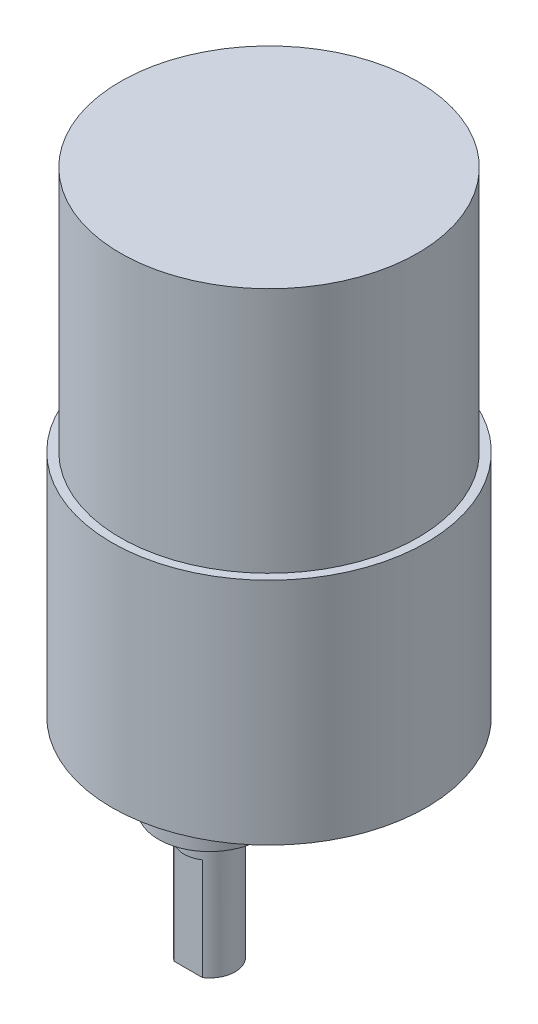
SolidWorks part; units mm, degrees
ref_plane "Ebene vorne" through (0, 0, 0) normal (0, 0, 1) x (1, 0, 0)
ref_plane "Ebene oben" through (0, 0, 0) normal (0, 1, 0) x (1, 0, 0)
ref_plane "Ebene rechts" through (0, 0, 0) normal (1, 0, 0) x (0, 0, -1)
sketch "Skizze1" plane through (0, 0, 0) normal (0, 1, 0) x (1, 0, 0)
  circle A0 centre (0, 0) radius 18.5
  dimension "D1" = 37
extrude "Aufsatz-Linear austragen1" add sketch "Skizze1" along normal blind 27
sketch "Skizze2" plane through (0, 27, 0) normal (0, 1, 0) x (1, 0, 0)
  circle A0 centre (0, 0) radius 17.5
  dimension "D1" = 35
extrude "Aufsatz-Linear austragen2" add sketch "Skizze2" along normal blind 29
sketch "Skizze3" plane through (0, 0, 0) normal (0, -1, 0) x (1, 0, 0)
  line L0 (0, 0) -> (50000, 0) construction
  line L1 (0, 0) -> (0, 50000) construction
  line L2 (7.75, -13.4234) -> (-7.75, 13.4234) construction
  line L3 (-7.75, -13.4234) -> (7.75, 13.4234) construction
  circle A0 centre (0, 0) radius 15.5 construction
  circle A1 centre (-15.5, 0) radius 1.5
  circle A2 centre (15.5, 0) radius 1.5
  circle A3 centre (7.75, 13.4234) radius 1.5
  circle A4 centre (-7.75, 13.4234) radius 1.5
  circle A5 centre (-7.75, -13.4234) radius 1.5
  circle A6 centre (7.75, -13.4234) radius 1.5
  point P14 (0, 0)
  point P17 (0, 0)
  point P21 (-18.9197, 0)
  dimension "D1" = 31
  dimension "D2" = 3
  dimension "D3" = 30
  dimension "D4" = 30
extrude "Schnitt-Linear austragen1" cut sketch "Skizze3" against normal blind 10
sketch "Skizze4" plane through (0, 0, 0) normal (0, -1, 0) x (1, 0, 0)
  line L0 (0, 0) -> (0, 18.5) construction
  circle A0 centre (0, 0) radius 18.5 construction
  circle A1 centre (0, 7) radius 6
  dimension "D1" = 12
  dimension "D2" = 7
extrude "Aufsatz-Linear austragen3" add sketch "Skizze4" along normal blind 6
sketch "Skizze5" plane through (0, -6, 0) normal (0, -1, 0) x (1, 0, 0)
  circle A0 centre (0, 7) radius 3
  dimension "D1" = 6
extrude "Aufsatz-Linear austragen4" add sketch "Skizze5" along normal blind 15
sketch "Skizze6" plane through (0, -21, 0) normal (0, -1, 0) x (1, 0, 0)
  line L0 (0, 7) -> (0, 10) construction
  line L1 (-3, 10.5) -> (3, 10.5)
  line L2 (-3, 10.5) -> (-3, 9.5)
  line L3 (-3, 9.5) -> (3, 9.5)
  line L4 (3, 10.5) -> (3, 9.5)
  line L5 (-3, 10.5) -> (3, 9.5) construction
  line L6 (-3, 9.5) -> (3, 10.5) construction
  circle A3 centre (0, 7) radius 3 construction
  circle A4 centre (0, 7) radius 3 construction
  point P0 (0, 10)
  point P11 (0, 0)
  point P13 (0, 0)
  dimension "D1" = 1
  dimension "D2" = 6
extrude "Schnitt-Linear austragen2" cut sketch "Skizze6" against normal blind 12
